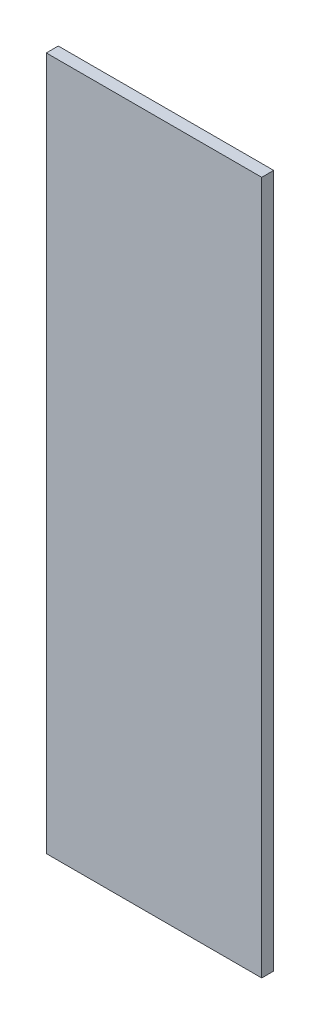
SolidWorks part; units mm, degrees
ref_plane "Front Plane" through (0, 0, 0) normal (0, 0, 1) x (1, 0, 0)
ref_plane "Top Plane" through (0, 0, 0) normal (0, 1, 0) x (1, 0, 0)
ref_plane "Right Plane" through (0, 0, 0) normal (1, 0, 0) x (0, 0, -1)
sketch "Sketch1" plane through (0, 0, 0) normal (0, 0, 1) x (1, 0, 0)
  line L1 (-57.15, 183.9595) -> (57.15, 183.9595)
  line L2 (-57.15, 183.9595) -> (-57.15, -183.9595)
  line L3 (-57.15, -183.9595) -> (57.15, -183.9595)
  line L4 (57.15, 183.9595) -> (57.15, -183.9595)
  line L5 (-57.15, 183.9595) -> (57.15, -183.9595) construction
  line L6 (-57.15, -183.9595) -> (57.15, 183.9595) construction
  point P0 (0, 0)
  dimension "D1" = 114.3
  dimension "D2" = 367.919
extrude "Boss-Extrude1" add sketch "Sketch1" along normal blind 6.35 contours L2 L3 L4 L1
